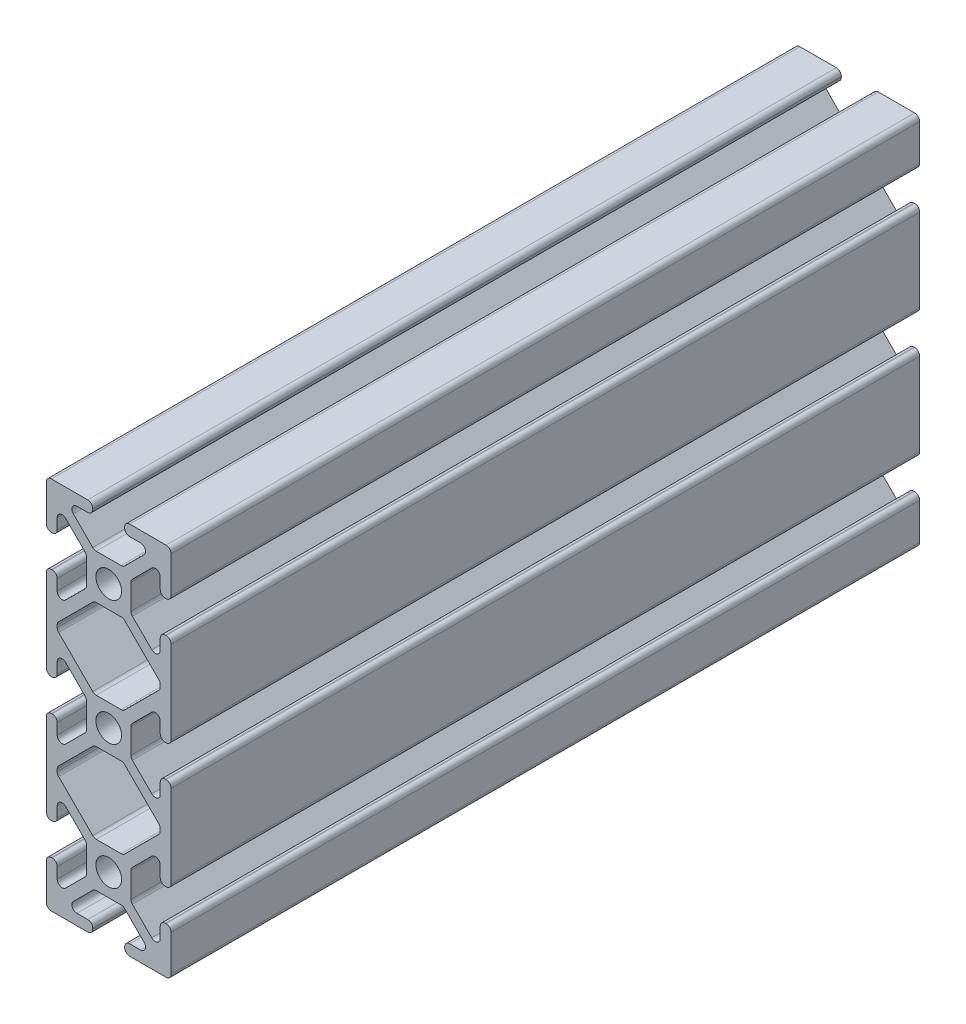
SolidWorks part; units mm, degrees
ref_plane "Front Plane" through (0, 0, 0) normal (0, 0, 1) x (1, 0, 0)
ref_plane "Top Plane" through (0, 0, 0) normal (0, 1, 0) x (1, 0, 0)
ref_plane "Right Plane" through (0, 0, 0) normal (1, 0, 0) x (0, 0, -1)
sketch "Sketch1" plane through (0, 0, 0) normal (0, 0, 1) x (1, 0, 0)
  line L0 (-12.7, 38.1) -> (-12.7, 12.7) construction
  line L1 (-12.7, -38.1) -> (12.7, -38.1) construction
  line L2 (-12.7, 12.7) -> (-12.7, -12.7) construction
  line L3 (-12.7, 38.1) -> (12.7, 38.1) construction
  line L4 (-12.7, -12.7) -> (-12.7, -38.1) construction
  line L5 (-12.7, -38.1) -> (12.7, 38.1) construction
  line L6 (-12.7, 38.1) -> (12.7, -38.1) construction
  line L7 (12.7, 38.1) -> (12.7, 12.7) construction
  line L8 (12.7, 12.7) -> (12.7, -12.7) construction
  line L9 (12.7, -12.7) -> (12.7, -38.1) construction
  line L10 (-12.7, 12.7) -> (12.7, 12.7) construction
  line L11 (-12.7, -12.7) -> (12.7, -12.7) construction
  line L12 (12.7, -12.7) -> (-12.7, -38.1) construction
  line L13 (12.7, -38.1) -> (-12.7, -12.7) construction
  line L14 (0, 38.1) -> (0, -38.1) construction
  line L15 (12.7, 12.7) -> (-12.7, 38.1) construction
  line L16 (12.7, 38.1) -> (-12.7, 12.7) construction
  line L17 (-12.7, 37.084) -> (-12.7, 29.6672)
  line L18 (-11.684, 28.6512) -> (-11.5062, 28.6512)
  line L19 (-10.4902, 29.6672) -> (-10.4902, 31.8748)
  line L20 (-8.7558, 32.5932) -> (-4.8188, 28.6562)
  line L21 (-4.5212, 27.9378) -> (-4.5212, 22.8622)
  line L22 (-4.8188, 22.1438) -> (-8.7558, 18.2068)
  line L23 (-10.4902, 18.9252) -> (-10.4902, 21.1328)
  line L24 (-11.5062, 22.1488) -> (-11.684, 22.1488)
  line L25 (-12.7, 21.1328) -> (-12.7, 4.2672)
  line L26 (-12.7, 0) -> (12.7, 0) construction
  line L27 (-12.7, -25.4) -> (12.7, -25.4) construction
  line L28 (-12.7, 25.4) -> (12.7, 25.4) construction
  line L29 (4.2672, 38.1) -> (11.684, 38.1)
  line L30 (3.2512, 36.9062) -> (3.2512, 37.084)
  line L31 (6.4748, 35.8902) -> (4.2672, 35.8902)
  line L32 (3.2562, 30.2188) -> (7.1932, 34.1558)
  line L33 (-2.5378, 29.9212) -> (2.5378, 29.9212)
  line L34 (-7.1932, 34.1558) -> (-3.2562, 30.2188)
  line L35 (-4.2672, 35.8902) -> (-6.4748, 35.8902)
  line L36 (-3.2512, 37.084) -> (-3.2512, 36.9062)
  line L37 (-11.684, 38.1) -> (-4.2672, 38.1)
  line L38 (4.5212, 2.5378) -> (4.5212, -2.5378)
  line L39 (11.5062, 22.1488) -> (11.684, 22.1488)
  line L40 (10.4902, 18.9252) -> (10.4902, 21.1328)
  line L41 (4.8188, 22.1438) -> (8.7558, 18.2068)
  line L42 (4.5212, 27.9378) -> (4.5212, 22.8622)
  line L43 (8.7558, 32.5932) -> (4.8188, 28.6562)
  line L44 (10.4902, 29.6672) -> (10.4902, 31.8748)
  line L45 (11.684, 28.6512) -> (11.5062, 28.6512)
  line L46 (12.7, 37.084) -> (12.7, 29.6672)
  line L47 (-10.4902, 12.4736) -> (-10.4902, 12.9264)
  line L48 (-10.1926, 13.6448) -> (-3.2562, 20.5812)
  line L49 (-2.5378, 20.8788) -> (2.5378, 20.8788)
  line L50 (10.4902, 12.4736) -> (10.4902, 12.9264)
  line L51 (10.1926, 13.6448) -> (3.2562, 20.5812)
  line L52 (10.1926, 11.7552) -> (3.2562, 4.8188)
  line L53 (-2.5378, 4.5212) -> (2.5378, 4.5212)
  line L54 (-10.1926, 11.7552) -> (-3.2562, 4.8188)
  line L55 (-2.5378, -4.5212) -> (2.5378, -4.5212)
  line L56 (-10.1926, -11.7552) -> (-3.2562, -4.8188)
  line L57 (10.1926, -11.7552) -> (3.2562, -4.8188)
  line L58 (10.4902, -12.4736) -> (10.4902, -12.9264)
  line L59 (10.1926, -13.6448) -> (3.2562, -20.5812)
  line L60 (-2.5378, -20.8788) -> (2.5378, -20.8788)
  line L61 (-10.1926, -13.6448) -> (-3.2562, -20.5812)
  line L62 (-10.4902, -12.4736) -> (-10.4902, -12.9264)
  line L63 (4.8188, -3.2562) -> (8.7558, -7.1932)
  line L64 (11.5062, -22.1488) -> (11.684, -22.1488)
  line L65 (10.4902, -18.9252) -> (10.4902, -21.1328)
  line L66 (4.8188, -22.1438) -> (8.7558, -18.2068)
  line L67 (4.5212, -27.9378) -> (4.5212, -22.8622)
  line L68 (8.7558, -32.5932) -> (4.8188, -28.6562)
  line L69 (10.4902, -29.6672) -> (10.4902, -31.8748)
  line L70 (11.684, -28.6512) -> (11.5062, -28.6512)
  line L71 (12.7, -37.084) -> (12.7, -29.6672)
  line L72 (3.2512, -36.9062) -> (3.2512, -37.084)
  line L73 (6.4748, -35.8902) -> (4.2672, -35.8902)
  line L74 (3.2562, -30.2188) -> (7.1932, -34.1558)
  line L75 (-2.5378, -29.9212) -> (2.5378, -29.9212)
  line L76 (-7.1932, -34.1558) -> (-3.2562, -30.2188)
  line L77 (-4.2672, -35.8902) -> (-6.4748, -35.8902)
  line L78 (-3.2512, -37.084) -> (-3.2512, -36.9062)
  line L79 (-11.684, -38.1) -> (-4.2672, -38.1)
  line L80 (4.2672, -38.1) -> (11.684, -38.1)
  line L81 (4.8188, 3.2562) -> (8.7558, 7.1932)
  line L82 (-11.5062, -22.1488) -> (-11.684, -22.1488)
  line L83 (-10.4902, -18.9252) -> (-10.4902, -21.1328)
  line L84 (-4.8188, -22.1438) -> (-8.7558, -18.2068)
  line L85 (-4.5212, -27.9378) -> (-4.5212, -22.8622)
  line L86 (-8.7558, -32.5932) -> (-4.8188, -28.6562)
  line L87 (-10.4902, -29.6672) -> (-10.4902, -31.8748)
  line L88 (-11.684, -28.6512) -> (-11.5062, -28.6512)
  line L89 (-12.7, -37.084) -> (-12.7, -29.6672)
  line L90 (-4.8188, 3.2562) -> (-8.7558, 7.1932)
  line L91 (-10.4902, 6.4748) -> (-10.4902, 4.2672)
  line L92 (-11.5062, 3.2512) -> (-11.684, 3.2512)
  line L93 (-4.5212, 2.5378) -> (-4.5212, -2.5378)
  line L94 (-12.7, -21.1328) -> (-12.7, -4.2672)
  line L95 (-4.8188, -3.2562) -> (-8.7558, -7.1932)
  line L96 (-10.4902, -6.4748) -> (-10.4902, -4.2672)
  line L97 (-11.5062, -3.2512) -> (-11.684, -3.2512)
  line L98 (10.4902, -6.4748) -> (10.4902, -4.2672)
  line L99 (10.4902, 6.4748) -> (10.4902, 4.2672)
  line L100 (11.5062, 3.2512) -> (11.684, 3.2512)
  line L101 (11.5062, -3.2512) -> (11.684, -3.2512)
  line L102 (12.7, -21.1328) -> (12.7, -4.2672)
  line L103 (12.7, 21.1328) -> (12.7, 4.2672)
  circle A0 centre (0, 25.4) radius 2.6035
  circle A1 centre (0, 0) radius 2.6035
  circle A2 centre (0, -25.4) radius 2.6035
  arc A3 (-12.7, 21.1328) -> (-11.684, 22.1488) centre (-11.684, 21.1328) cw
  arc A4 (-11.5062, 22.1488) -> (-10.4902, 21.1328) centre (-11.5062, 21.1328) cw
  arc A5 (-10.4902, 18.9252) -> (-8.7558, 18.2068) centre (-9.4742, 18.9252) ccw
  arc A6 (-4.8188, 22.1438) -> (-4.5212, 22.8622) centre (-5.5372, 22.8622) ccw
  arc A7 (-4.5212, 27.9378) -> (-4.8188, 28.6562) centre (-5.5372, 27.9378) ccw
  arc A8 (-8.7558, 32.5932) -> (-10.4902, 31.8748) centre (-9.4742, 31.8748) ccw
  arc A9 (-10.4902, 29.6672) -> (-11.5062, 28.6512) centre (-11.5062, 29.6672) cw
  arc A10 (-11.684, 28.6512) -> (-12.7, 29.6672) centre (-11.684, 29.6672) cw
  arc A11 (4.2672, 38.1) -> (3.2512, 37.084) centre (4.2672, 37.084) ccw
  arc A12 (3.2512, 36.9062) -> (4.2672, 35.8902) centre (4.2672, 36.9062) ccw
  arc A13 (6.4748, 35.8902) -> (7.1932, 34.1558) centre (6.4748, 34.8742) cw
  arc A14 (3.2562, 30.2188) -> (2.5378, 29.9212) centre (2.5378, 30.9372) cw
  arc A15 (-2.5378, 29.9212) -> (-3.2562, 30.2188) centre (-2.5378, 30.9372) cw
  arc A16 (-7.1932, 34.1558) -> (-6.4748, 35.8902) centre (-6.4748, 34.8742) cw
  arc A17 (-4.2672, 35.8902) -> (-3.2512, 36.9062) centre (-4.2672, 36.9062) ccw
  arc A18 (-3.2512, 37.084) -> (-4.2672, 38.1) centre (-4.2672, 37.084) ccw
  arc A19 (12.7, 21.1328) -> (11.684, 22.1488) centre (11.684, 21.1328) ccw
  arc A20 (11.5062, 22.1488) -> (10.4902, 21.1328) centre (11.5062, 21.1328) ccw
  arc A21 (10.4902, 18.9252) -> (8.7558, 18.2068) centre (9.4742, 18.9252) cw
  arc A22 (4.8188, 22.1438) -> (4.5212, 22.8622) centre (5.5372, 22.8622) cw
  arc A23 (4.5212, 27.9378) -> (4.8188, 28.6562) centre (5.5372, 27.9378) cw
  arc A24 (8.7558, 32.5932) -> (10.4902, 31.8748) centre (9.4742, 31.8748) cw
  arc A25 (10.4902, 29.6672) -> (11.5062, 28.6512) centre (11.5062, 29.6672) ccw
  arc A26 (11.684, 28.6512) -> (12.7, 29.6672) centre (11.684, 29.6672) ccw
  arc A27 (12.7, 37.084) -> (11.684, 38.1) centre (11.684, 37.084) ccw
  arc A28 (-11.684, 38.1) -> (-12.7, 37.084) centre (-11.684, 37.084) ccw
  arc A29 (-10.1926, 13.6448) -> (-10.4902, 12.9264) centre (-9.4742, 12.9264) ccw
  arc A30 (-2.5378, 20.8788) -> (-3.2562, 20.5812) centre (-2.5378, 19.8628) ccw
  arc A31 (10.1926, 13.6448) -> (10.4902, 12.9264) centre (9.4742, 12.9264) cw
  arc A32 (2.5378, 20.8788) -> (3.2562, 20.5812) centre (2.5378, 19.8628) cw
  arc A33 (10.1926, 11.7552) -> (10.4902, 12.4736) centre (9.4742, 12.4736) ccw
  arc A34 (2.5378, 4.5212) -> (3.2562, 4.8188) centre (2.5378, 5.5372) ccw
  arc A35 (-2.5378, 4.5212) -> (-3.2562, 4.8188) centre (-2.5378, 5.5372) cw
  arc A36 (-10.1926, 11.7552) -> (-10.4902, 12.4736) centre (-9.4742, 12.4736) cw
  arc A37 (2.5378, -4.5212) -> (3.2562, -4.8188) centre (2.5378, -5.5372) cw
  arc A38 (-2.5378, -4.5212) -> (-3.2562, -4.8188) centre (-2.5378, -5.5372) ccw
  arc A39 (10.1926, -11.7552) -> (10.4902, -12.4736) centre (9.4742, -12.4736) cw
  arc A40 (10.1926, -13.6448) -> (10.4902, -12.9264) centre (9.4742, -12.9264) ccw
  arc A41 (2.5378, -20.8788) -> (3.2562, -20.5812) centre (2.5378, -19.8628) ccw
  arc A42 (-2.5378, -20.8788) -> (-3.2562, -20.5812) centre (-2.5378, -19.8628) cw
  arc A43 (-10.1926, -13.6448) -> (-10.4902, -12.9264) centre (-9.4742, -12.9264) cw
  arc A44 (-10.1926, -11.7552) -> (-10.4902, -12.4736) centre (-9.4742, -12.4736) ccw
  arc A45 (12.7, -21.1328) -> (11.684, -22.1488) centre (11.684, -21.1328) cw
  arc A46 (11.5062, -22.1488) -> (10.4902, -21.1328) centre (11.5062, -21.1328) cw
  arc A47 (10.4902, -18.9252) -> (8.7558, -18.2068) centre (9.4742, -18.9252) ccw
  arc A48 (4.8188, -22.1438) -> (4.5212, -22.8622) centre (5.5372, -22.8622) ccw
  arc A49 (4.5212, -27.9378) -> (4.8188, -28.6562) centre (5.5372, -27.9378) ccw
  arc A50 (8.7558, -32.5932) -> (10.4902, -31.8748) centre (9.4742, -31.8748) ccw
  arc A51 (10.4902, -29.6672) -> (11.5062, -28.6512) centre (11.5062, -29.6672) cw
  arc A52 (11.684, -28.6512) -> (12.7, -29.6672) centre (11.684, -29.6672) cw
  arc A53 (4.2672, -38.1) -> (3.2512, -37.084) centre (4.2672, -37.084) cw
  arc A54 (3.2512, -36.9062) -> (4.2672, -35.8902) centre (4.2672, -36.9062) cw
  arc A55 (6.4748, -35.8902) -> (7.1932, -34.1558) centre (6.4748, -34.8742) ccw
  arc A56 (3.2562, -30.2188) -> (2.5378, -29.9212) centre (2.5378, -30.9372) ccw
  arc A57 (-2.5378, -29.9212) -> (-3.2562, -30.2188) centre (-2.5378, -30.9372) ccw
  arc A58 (-7.1932, -34.1558) -> (-6.4748, -35.8902) centre (-6.4748, -34.8742) ccw
  arc A59 (-4.2672, -35.8902) -> (-3.2512, -36.9062) centre (-4.2672, -36.9062) cw
  arc A60 (-3.2512, -37.084) -> (-4.2672, -38.1) centre (-4.2672, -37.084) cw
  arc A61 (12.7, -37.084) -> (11.684, -38.1) centre (11.684, -37.084) cw
  arc A62 (-12.7, -21.1328) -> (-11.684, -22.1488) centre (-11.684, -21.1328) ccw
  arc A63 (-11.5062, -22.1488) -> (-10.4902, -21.1328) centre (-11.5062, -21.1328) ccw
  arc A64 (-10.4902, -18.9252) -> (-8.7558, -18.2068) centre (-9.4742, -18.9252) cw
  arc A65 (-4.8188, -22.1438) -> (-4.5212, -22.8622) centre (-5.5372, -22.8622) cw
  arc A66 (-4.5212, -27.9378) -> (-4.8188, -28.6562) centre (-5.5372, -27.9378) cw
  arc A67 (-8.7558, -32.5932) -> (-10.4902, -31.8748) centre (-9.4742, -31.8748) cw
  arc A68 (-10.4902, -29.6672) -> (-11.5062, -28.6512) centre (-11.5062, -29.6672) ccw
  arc A69 (-11.684, -28.6512) -> (-12.7, -29.6672) centre (-11.684, -29.6672) ccw
  arc A70 (-11.684, -38.1) -> (-12.7, -37.084) centre (-11.684, -37.084) cw
  arc A71 (-4.8188, 3.2562) -> (-4.5212, 2.5378) centre (-5.5372, 2.5378) cw
  arc A72 (-10.4902, 6.4748) -> (-8.7558, 7.1932) centre (-9.4742, 6.4748) cw
  arc A73 (-11.5062, 3.2512) -> (-10.4902, 4.2672) centre (-11.5062, 4.2672) ccw
  arc A74 (-12.7, 4.2672) -> (-11.684, 3.2512) centre (-11.684, 4.2672) ccw
  arc A75 (-4.8188, -3.2562) -> (-4.5212, -2.5378) centre (-5.5372, -2.5378) ccw
  arc A76 (-10.4902, -6.4748) -> (-8.7558, -7.1932) centre (-9.4742, -6.4748) ccw
  arc A77 (-11.5062, -3.2512) -> (-10.4902, -4.2672) centre (-11.5062, -4.2672) cw
  arc A78 (-12.7, -4.2672) -> (-11.684, -3.2512) centre (-11.684, -4.2672) cw
  arc A79 (4.8188, 3.2562) -> (4.5212, 2.5378) centre (5.5372, 2.5378) ccw
  arc A80 (4.8188, -3.2562) -> (4.5212, -2.5378) centre (5.5372, -2.5378) cw
  arc A81 (10.4902, 6.4748) -> (8.7558, 7.1932) centre (9.4742, 6.4748) ccw
  arc A82 (10.4902, -6.4748) -> (8.7558, -7.1932) centre (9.4742, -6.4748) cw
  arc A83 (11.5062, -3.2512) -> (10.4902, -4.2672) centre (11.5062, -4.2672) ccw
  arc A84 (11.5062, 3.2512) -> (10.4902, 4.2672) centre (11.5062, 4.2672) cw
  arc A85 (12.7, -4.2672) -> (11.684, -3.2512) centre (11.684, -4.2672) ccw
  arc A86 (12.7, 4.2672) -> (11.684, 3.2512) centre (11.684, 4.2672) cw
  point P0 (0, 0)
  point P26 (-12.7, 22.1488)
  point P41 (-12.7, 28.6512)
  point P107 (-6.7244, 17.113)
  point P120 (0, 20.8788)
  point P121 (10.4902, 12.7)
  point P132 (-10.4902, 12.7)
  point P249 (-4.5212, 0)
  dimension "D2" = 5.207
  dimension "D8" = 1.016
  dimension "D9" = 3.2512
  dimension "D10" = 1.1049
  dimension "D1" = 25.4
  dimension "D3" = 2.2098
  dimension "D4" = 6.5024
  dimension "D5" = 4.5212
  dimension "D6" = 1.1049
  dimension "D7" = 1.1049
  dimension "D11" = 4.5212
extrude "Main Extrusion" add sketch "Sketch1" along normal mid plane 152.4
sketch "Sketch2" plane through (0, 0, 76.2) normal (0, 0, 1) x (1, 0, 0)
  line L0 (-4.2672, 38.1) -> (-11.684, 38.1) construction
  line L1 (-12.7, -38.1) -> (12.7, -38.1) construction
  line L2 (-12.7, 38.1) -> (-12.7, 12.7) construction
  line L3 (-12.7, 38.1) -> (12.7, 38.1) construction
  line L4 (-12.7, 21.1328) -> (-12.7, 4.2672) construction
  line L5 (-12.7, -38.1) -> (12.7, 38.1) construction
  line L6 (-12.7, 38.1) -> (12.7, -38.1) construction
  line L7 (-12.7, 12.7) -> (-12.7, -12.7) construction
  line L8 (0, 38.1) -> (0, -38.1) construction
  line L9 (-12.7, -4.2672) -> (-12.7, -21.1328) construction
  line L10 (-12.7, -12.7) -> (-12.7, -38.1) construction
  line L11 (12.7, 38.1) -> (12.7, 12.7) construction
  line L12 (12.7, 4.2672) -> (12.7, 21.1328) construction
  line L13 (12.7, 12.7) -> (12.7, -12.7) construction
  line L14 (12.7, -21.1328) -> (12.7, -4.2672) construction
  line L15 (12.7, -12.7) -> (12.7, -38.1) construction
  line L16 (-12.7, 25.4) -> (12.7, 25.4) construction
  line L17 (-12.7, 0) -> (12.7, 0) construction
  line L18 (-12.7, -25.4) -> (12.7, -25.4) construction
  line L19 (-12.7, 12.7) -> (12.7, 12.7) construction
  line L20 (-12.7, -12.7) -> (12.7, -12.7) construction
  line L21 (-3.2512, 36.9062) -> (-3.2512, 37.084) construction
  line L22 (-10.4902, 38.1) -> (-9.4742, 38.1)
  line L23 (-6.477, 38.1) -> (-5.461, 38.1)
  line L24 (-12.7, 38.1) -> (12.7, 12.7) construction
  line L25 (12.7, 12.7) -> (-12.7, -12.7) construction
  line L26 (-12.7, -12.7) -> (12.7, -38.1) construction
  line L27 (-12.7, -38.1) -> (12.7, -12.7) construction
  line L28 (12.7, -12.7) -> (-12.7, 12.7) construction
  line L29 (-12.7, 12.7) -> (12.7, 38.1) construction
  line L30 (6.477, 38.1) -> (5.461, 38.1)
  line L31 (10.4902, 38.1) -> (9.4742, 38.1)
  line L32 (-12.7, 14.9098) -> (-12.7, 15.9258)
  line L33 (-12.7, 18.923) -> (-12.7, 19.939)
  line L34 (-12.7, 31.877) -> (-12.7, 30.861)
  line L35 (-12.7, 35.8902) -> (-12.7, 34.8742)
  line L36 (12.7, 35.8902) -> (12.7, 34.8742)
  line L37 (12.7, 31.877) -> (12.7, 30.861)
  line L38 (12.7, 18.923) -> (12.7, 19.939)
  line L39 (12.7, 14.9098) -> (12.7, 15.9258)
  line L40 (12.7, 10.4902) -> (12.7, 9.4742)
  line L41 (12.7, 6.477) -> (12.7, 5.461)
  line L42 (-12.7, 10.4902) -> (-12.7, 9.4742)
  line L43 (-12.7, 6.477) -> (-12.7, 5.461)
  line L44 (12.7, -6.477) -> (12.7, -5.461)
  line L45 (12.7, -10.4902) -> (12.7, -9.4742)
  line L46 (12.7, -14.9098) -> (12.7, -15.9258)
  line L47 (12.7, -18.923) -> (12.7, -19.939)
  line L48 (12.7, -31.877) -> (12.7, -30.861)
  line L49 (12.7, -35.8902) -> (12.7, -34.8742)
  line L50 (10.4902, -38.1) -> (9.4742, -38.1)
  line L51 (6.477, -38.1) -> (5.461, -38.1)
  line L52 (-6.477, -38.1) -> (-5.461, -38.1)
  line L53 (-10.4902, -38.1) -> (-9.4742, -38.1)
  line L54 (-12.7, -35.8902) -> (-12.7, -34.8742)
  line L55 (-12.7, -31.877) -> (-12.7, -30.861)
  line L56 (-12.7, -18.923) -> (-12.7, -19.939)
  line L57 (-12.7, -14.9098) -> (-12.7, -15.9258)
  line L58 (-12.7, -10.4902) -> (-12.7, -9.4742)
  line L59 (-12.7, -6.477) -> (-12.7, -5.461)
  arc A0 (-10.4902, 38.1) -> (-9.4742, 38.1) centre (-9.9822, 38.1) ccw
  arc A1 (-6.477, 38.1) -> (-5.461, 38.1) centre (-5.969, 38.1) ccw
  arc A2 (6.477, 38.1) -> (5.461, 38.1) centre (5.969, 38.1) cw
  arc A3 (10.4902, 38.1) -> (9.4742, 38.1) centre (9.9822, 38.1) cw
  arc A4 (-12.7, 14.9098) -> (-12.7, 15.9258) centre (-12.7, 15.4178) ccw
  arc A5 (-12.7, 18.923) -> (-12.7, 19.939) centre (-12.7, 19.431) ccw
  arc A6 (-12.7, 31.877) -> (-12.7, 30.861) centre (-12.7, 31.369) cw
  arc A7 (-12.7, 35.8902) -> (-12.7, 34.8742) centre (-12.7, 35.3822) cw
  arc A8 (12.7, 35.8902) -> (12.7, 34.8742) centre (12.7, 35.3822) ccw
  arc A9 (12.7, 31.877) -> (12.7, 30.861) centre (12.7, 31.369) ccw
  arc A10 (12.7, 18.923) -> (12.7, 19.939) centre (12.7, 19.431) cw
  arc A11 (12.7, 14.9098) -> (12.7, 15.9258) centre (12.7, 15.4178) cw
  arc A12 (12.7, 10.4902) -> (12.7, 9.4742) centre (12.7, 9.9822) ccw
  arc A13 (12.7, 6.477) -> (12.7, 5.461) centre (12.7, 5.969) ccw
  arc A14 (-12.7, 10.4902) -> (-12.7, 9.4742) centre (-12.7, 9.9822) cw
  arc A15 (-12.7, 6.477) -> (-12.7, 5.461) centre (-12.7, 5.969) cw
  arc A16 (12.7, -6.477) -> (12.7, -5.461) centre (12.7, -5.969) cw
  arc A17 (12.7, -10.4902) -> (12.7, -9.4742) centre (12.7, -9.9822) cw
  arc A18 (12.7, -14.9098) -> (12.7, -15.9258) centre (12.7, -15.4178) ccw
  arc A19 (12.7, -18.923) -> (12.7, -19.939) centre (12.7, -19.431) ccw
  arc A20 (12.7, -31.877) -> (12.7, -30.861) centre (12.7, -31.369) cw
  arc A21 (12.7, -35.8902) -> (12.7, -34.8742) centre (12.7, -35.3822) cw
  arc A22 (10.4902, -38.1) -> (9.4742, -38.1) centre (9.9822, -38.1) ccw
  arc A23 (6.477, -38.1) -> (5.461, -38.1) centre (5.969, -38.1) ccw
  arc A24 (-6.477, -38.1) -> (-5.461, -38.1) centre (-5.969, -38.1) cw
  arc A25 (-10.4902, -38.1) -> (-9.4742, -38.1) centre (-9.9822, -38.1) cw
  arc A26 (-12.7, -35.8902) -> (-12.7, -34.8742) centre (-12.7, -35.3822) ccw
  arc A27 (-12.7, -31.877) -> (-12.7, -30.861) centre (-12.7, -31.369) ccw
  arc A28 (-12.7, -18.923) -> (-12.7, -19.939) centre (-12.7, -19.431) cw
  arc A29 (-12.7, -14.9098) -> (-12.7, -15.9258) centre (-12.7, -15.4178) cw
  arc A30 (-12.7, -10.4902) -> (-12.7, -9.4742) centre (-12.7, -9.9822) ccw
  arc A31 (-12.7, -6.477) -> (-12.7, -5.461) centre (-12.7, -5.969) ccw
  point P0 (0, 0)
  dimension "D1" = 0.508
  dimension "D2" = 2.2098
  dimension "D3" = 2.2098
